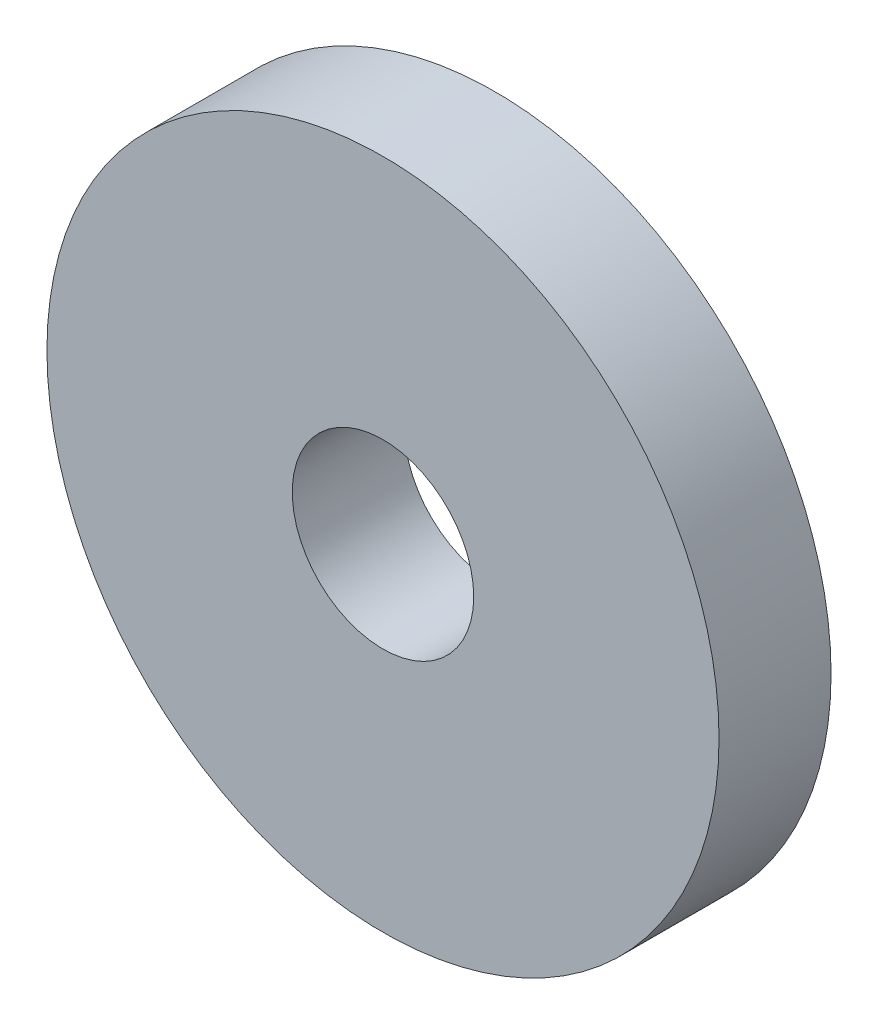
SolidWorks part; units mm, degrees
material "Balsa"
ref_plane "Front Plane" through (0, 0, 0) normal (0, 0, 1) x (1, 0, 0)
ref_plane "Top Plane" through (0, 0, 0) normal (0, 1, 0) x (1, 0, 0)
ref_plane "Right Plane" through (0, 0, 0) normal (1, 0, 0) x (0, 0, -1)
sketch "Sketch1" plane through (0, 0, 0) normal (0, 0, 1) x (1, 0, 0)
  circle A0 centre (0, 0) radius 4.05
  circle A1 centre (0, 0) radius 15
  dimension "D1" = 30
  dimension "D2" = 8.1
extrude "Boss-Extrude1" add sketch "Sketch1" along normal blind 5
